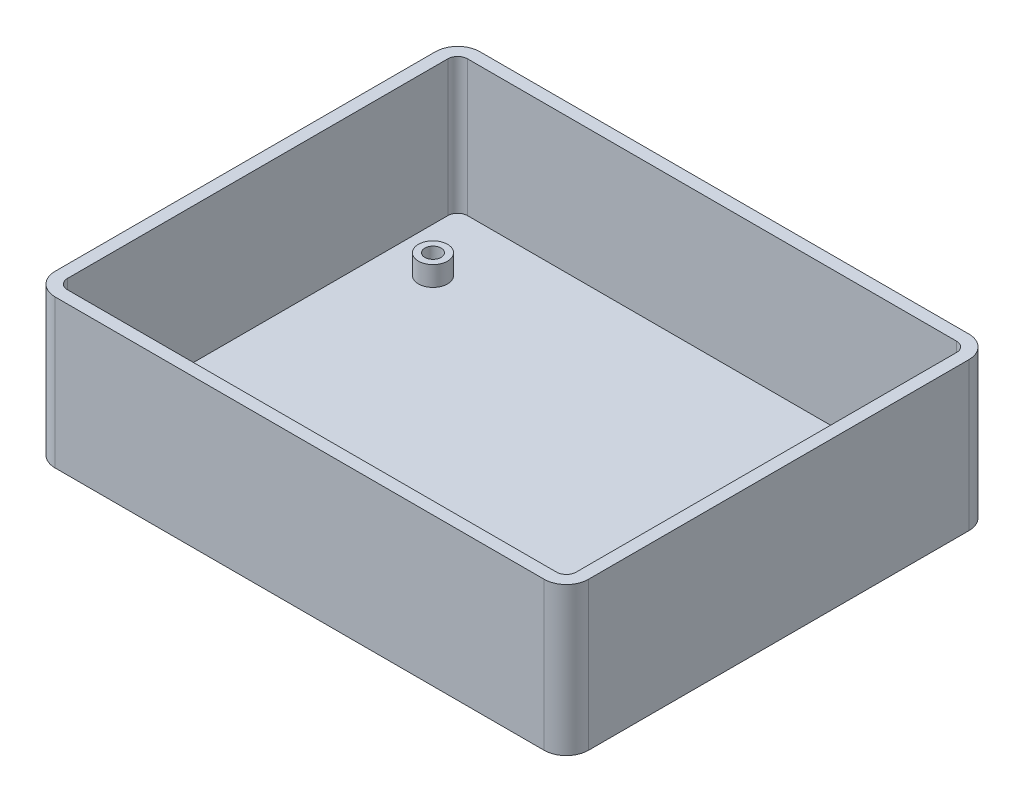
SolidWorks part; units mm, degrees
ref_plane "前视基准面" through (0, 0, 0) normal (0, 0, 1) x (1, 0, 0)
ref_plane "上视基准面" through (0, 0, 0) normal (0, 1, 0) x (1, 0, 0)
ref_plane "右视基准面" through (0, 0, 0) normal (1, 0, 0) x (0, 0, -1)
sketch "草图1" plane through (0, 0, 0) normal (0, 1, 0) x (1, 0, 0)
  line L1 (-45, -35) -> (45, -35) construction
  line L2 (-45, -35) -> (-45, 35) construction
  line L3 (-45, 35) -> (45, 35) construction
  line L4 (45, -35) -> (45, 35) construction
  line L5 (-45, -35) -> (45, 35) construction
  line L6 (-45, 35) -> (45, -35) construction
  line L7 (41, -31) -> (-41, -31) construction
  line L8 (41, -31) -> (41, 31) construction
  line L9 (41, 31) -> (-41, 31) construction
  line L10 (-41, -31) -> (-41, 31) construction
  line L11 (41, -31) -> (-41, 31) construction
  line L12 (41, 31) -> (-41, -31) construction
  line L13 (-50, 45) -> (53, 45)
  line L14 (-50, 45) -> (-50, -36)
  line L15 (-50, -36) -> (53, -36)
  line L16 (53, 45) -> (53, -36)
  circle A0 centre (41, 31) radius 1.65
  circle A1 centre (41, -31) radius 1.65
  circle A2 centre (-41, -31) radius 1.65
  circle A3 centre (-41, 31) radius 1.65
  point P0 (0, 0)
  point P6 (0, 0)
  dimension "D5" = 3.3
  dimension "D1" = 70
  dimension "D2" = 90
  dimension "D3" = 62
  dimension "D4" = 82
  dimension "D6" = 5
  dimension "D7" = 8
  dimension "D8" = 10
  dimension "D9" = 1
extrude "凸台-拉伸1" add sketch "草图1" along normal blind 2.5
fillet "圆角1" radius 2 4 edges at (53, 1.25, 36) (53, 1.25, -45) (-50, 1.25, 36) (-50, 1.25, -45)
sketch "草图4" plane through (0, 0, 0) normal (0, -1, 0) x (1, 0, 0)
  line L0 (51, 38.5) -> (-48, 38.5)
  line L1 (-52.5, 34) -> (-52.5, -43)
  line L2 (-48, -47.5) -> (51, -47.5)
  line L3 (55.5, -43) -> (55.5, 34)
  line L4 (51, 36) -> (-48, 36)
  line L5 (53, -43) -> (53, 34)
  line L6 (-48, -45) -> (51, -45)
  line L7 (-50, 34) -> (-50, -43)
  line L8 (51, 36) -> (-48, 36)
  line L9 (53, -43) -> (53, 34)
  line L10 (-48, -45) -> (51, -45)
  line L11 (-50, 34) -> (-50, -43)
  arc A0 (-48, 38.5) -> (-52.5, 34) centre (-48, 34) ccw
  arc A1 (-52.5, -43) -> (-48, -47.5) centre (-48, -43) ccw
  arc A2 (51, -47.5) -> (55.5, -43) centre (51, -43) ccw
  arc A3 (55.5, 34) -> (51, 38.5) centre (51, 34) ccw
  arc A4 (53, 34) -> (51, 36) centre (51, 34) ccw
  arc A5 (51, -45) -> (53, -43) centre (51, -43) ccw
  arc A6 (-50, -43) -> (-48, -45) centre (-48, -43) ccw
  arc A7 (-48, 36) -> (-50, 34) centre (-48, 34) ccw
  arc A8 (53, 34) -> (51, 36) centre (51, 34) ccw
  arc A9 (51, -45) -> (53, -43) centre (51, -43) ccw
  arc A10 (-50, -43) -> (-48, -45) centre (-48, -43) ccw
  arc A11 (-48, 36) -> (-50, 34) centre (-48, 34) ccw
  dimension "D1" = 0
  dimension "D2" = 2.5
extrude "凸台-拉伸2" add sketch "草图4" against normal blind 30
sketch "草图5" plane through (0, 2.5, 0) normal (0, 1, 0) x (1, 0, 0)
  circle A0 centre (-41, -31) radius 1.65 construction
  circle A1 centre (41, -31) radius 1.65 construction
  circle A2 centre (41, 31) radius 1.65 construction
  circle A3 centre (-41, 31) radius 1.65 construction
  circle A4 centre (-41, -31) radius 1.65
  circle A5 centre (41, -31) radius 1.65
  circle A6 centre (41, 31) radius 1.65
  circle A7 centre (-41, 31) radius 1.65
  circle A8 centre (-41, -31) radius 2.95
  circle A9 centre (41, -31) radius 2.95
  circle A10 centre (41, 31) radius 2.95
  circle A11 centre (-41, 31) radius 2.95
  dimension "D1" = 1.3
extrude "凸台-拉伸3" add sketch "草图5" along normal blind 4
